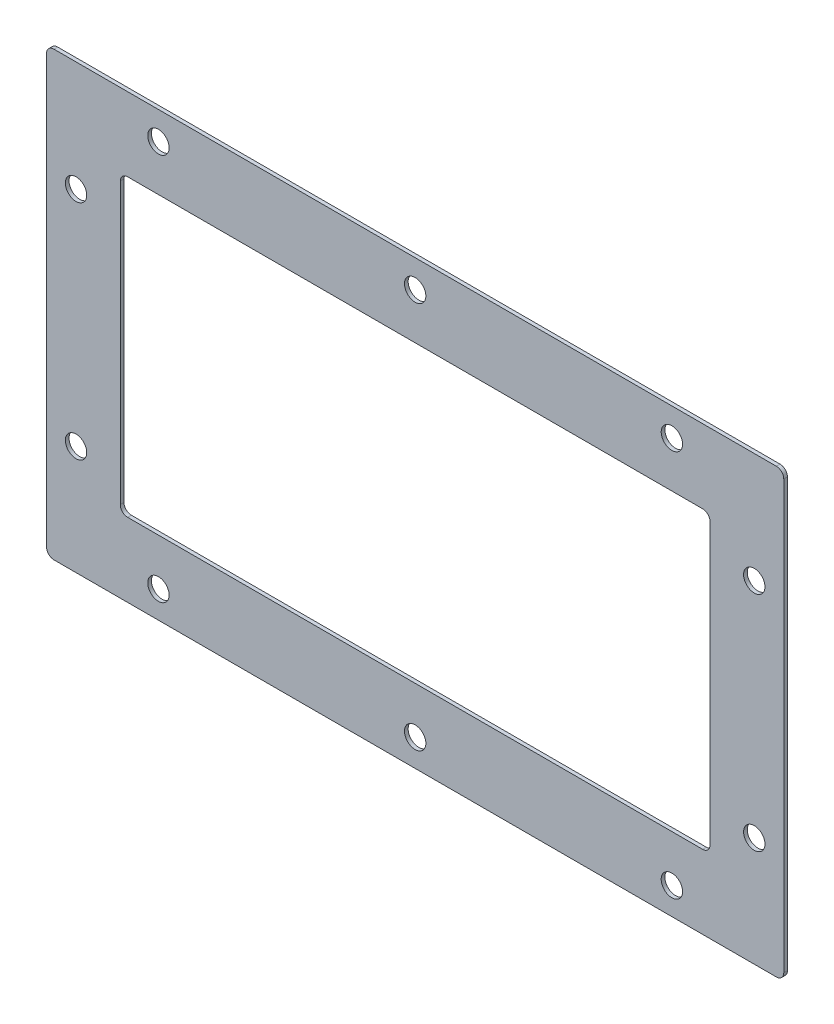
SolidWorks part; units mm, degrees
ref_plane "Front Plane" through (0, 0, 0) normal (0, 0, 1) x (1, 0, 0)
ref_plane "Top Plane" through (0, 0, 0) normal (0, 1, 0) x (1, 0, 0)
ref_plane "Right Plane" through (0, 0, 0) normal (1, 0, 0) x (0, 0, -1)
sketch "Sketch1" plane through (0, 0, 0) normal (0, 0, 1) x (1, 0, 0)
  line L1 (80, -40) -> (-80, -40)
  line L2 (80, -40) -> (80, 40)
  line L3 (80, 40) -> (-80, 40)
  line L4 (-80, -40) -> (-80, 40)
  line L5 (80, -40) -> (-80, 40) construction
  line L6 (80, 40) -> (-80, -40) construction
  line L7 (100, -60) -> (-100, -60)
  line L8 (100, -60) -> (100, 60)
  line L9 (100, 60) -> (-100, 60)
  line L10 (-100, -60) -> (-100, 60)
  line L11 (100, -60) -> (-100, 60) construction
  line L12 (100, 60) -> (-100, -60) construction
  point P0 (0, 0)
  point P6 (0, 0)
  dimension "D1" = 200
  dimension "D2" = 120
  dimension "D3" = 20
  dimension "D4" = 20
extrude "Boss-Extrude1" add sketch "Sketch1" along normal blind 1
fillet "Fillet1" radius 2 8 edges at (80, -40, 0.5) (-80, 40, 0.5) (-80, -40, 0.5) (80, 40, 0.5) (-100, 60, 0.5) (100, -60, 0.5) (-100, -60, 0.5) (100, 60, 0.5)
hole_wizard "M5 Clearance Hole1" positions "Sketch2" profile "Sketch3" hole size "M5" standard "ISO" end condition through all
sketch "Sketch2" plane through (0, 0, 1) normal (0, 0, 1) x (1, 0, 0)
  point P0 (92, -30.3341)
  point P3 (69.6464, -52.6628)
  point P6 (92, 30.1071)
  point P9 (0, -52.6628)
  point P12 (69.6464, 52.4357)
  point P15 (0, 52.4357)
  point P18 (-69.6464, 52.4357)
  point P21 (-92, 30.1071)
  point P24 (-92, -30.3341)
  point P27 (-69.6464, -52.6628)
sketch "Sketch3" plane through (92, -30.3341, 1) normal (1, 0, 0) x (0, -1, 0)
  line L0 (0, 0) -> (0, 1)
  line L1 (0, 1) -> (2.9, 1)
  line L2 (2.9, 1) -> (2.9, 0)
  line L5 (2.9, 0) -> (0, 0)
  line L11 (0, -6.35) -> (0, 107.95) construction
  dimension "Thru Hole Dia." = 5.8
  dimension "Thru Hole Depth" = 1
